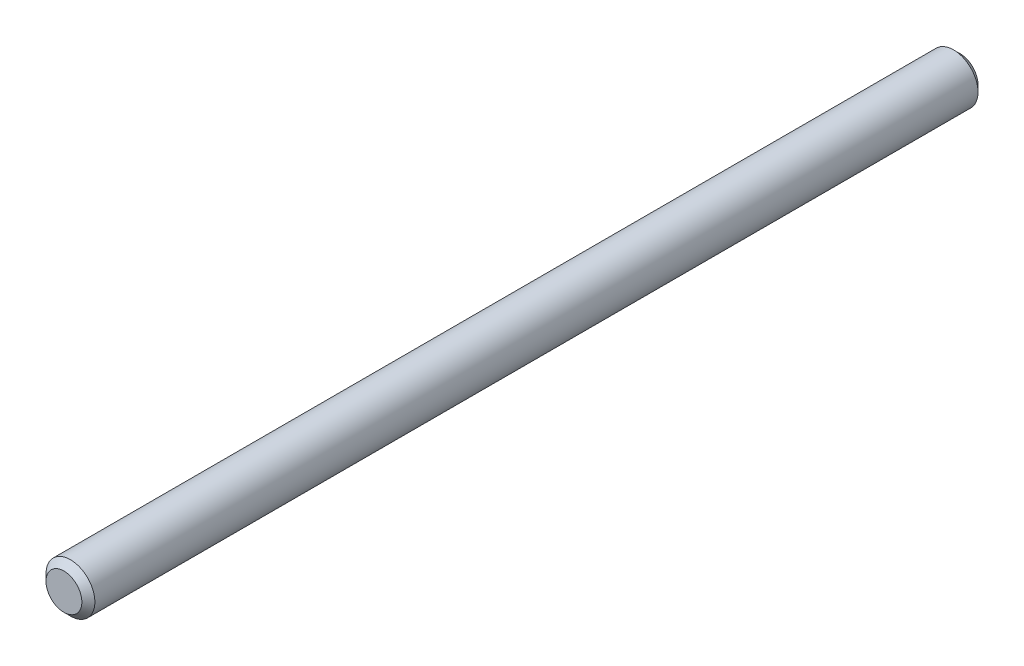
SolidWorks part; units mm, degrees
ref_plane "Front Plane" through (0, 0, 0) normal (0, 0, 1) x (1, 0, 0)
ref_plane "Top Plane" through (0, 0, 0) normal (0, 1, 0) x (1, 0, 0)
ref_plane "Right Plane" through (0, 0, 0) normal (1, 0, 0) x (0, 0, -1)
sketch "Sketch2" plane through (0, 0, 0) normal (0, 0, 1) x (1, 0, 0)
  circle A0 centre (0, 0) radius 7.5
  dimension "D1" = 15
extrude "Boss-Extrude1" add sketch "Sketch2" along normal mid plane 275
chamfer "Chamfer1" distance 2 angle 45 2 edges at (7.5, 0, -137.5) (7.5, 0, 137.5)
